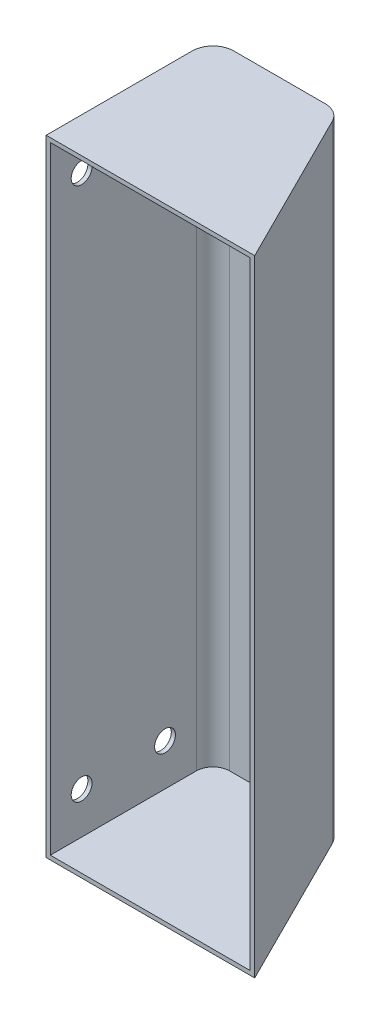
SolidWorks part; units mm, degrees
material "6061-T6 (SS)"
ref_plane "Front Plane" through (0, 0, 0) normal (1, 0, 0) x (0, 1, 0)
ref_plane "Top Plane" through (0, 0, 0) normal (0, 0, 1) x (0, 1, 0)
ref_plane "Right Plane" through (0, 0, 0) normal (0, 1, 0) x (-1, 0, 0)
sketch "Sketch2" plane through (0, 0, 0) normal (0, 1, 0) x (-1, 0, 0)
  line L0 (0, -1430.1125) -> (0, 70075.5127) construction
  line L1 (-1430.1125, 0) -> (70075.5127, 0) construction
  line L2 (0, 40) -> (0, 5)
  line L3 (-5, 0) -> (-26.9098, 0)
  line L4 (-31.382, 2.7639) -> (-50, 40)
  line L5 (-50, 40) -> (0, 40)
  arc A0 (0, 5) -> (-5, 0) centre (-5, 5) cw
  arc A1 (-26.9098, 0) -> (-31.382, 2.7639) centre (-26.9098, 5) cw
  point P7 (0, 0)
  point P10 (-31.5304, 0)
  point P11 (-49.8113, 40)
  point P14 (0, 0)
  point P17 (-30, 0)
  dimension "D4" = 5
  dimension "D1" = 40
  dimension "D2" = 30
  dimension "D3" = 50
extrude "Boss-Extrude1" add sketch "Sketch2" along normal mid plane 150
shell "Shell1" thickness 1
sketch "Sketch3" plane through (1, 0, 0) normal (1, 0, 0) x (0, 1, 0)
  line L0 (0, -1000) -> (0, 49000) construction
  line L1 (-1000, 22.5) -> (49000, 22.5) construction
  line L4 (-74, 40) -> (-74, 5)
  line L5 (-74, 5) -> (74, 5)
  line L6 (74, 5) -> (74, 40)
  line L7 (74, 40) -> (-74, 40)
  line L8 (-74, 40) -> (-74, 5) construction
  line L9 (-74, 5) -> (74, 5) construction
  line L10 (74, 5) -> (74, 40) construction
  line L11 (74, 40) -> (-74, 40) construction
  circle A0 centre (-64, 32.5) radius 2.5
  circle A1 centre (-64, 12.5) radius 2.5
  circle A2 centre (64, 12.5) radius 2.5
  circle A3 centre (64, 32.5) radius 2.5
  point P10 (74, 22.5)
  dimension "D4" = 5
  dimension "D2" = 10
  dimension "D3" = 10
  dimension "D1" = 0
extrude "Cut-Extrude1" cut sketch "Sketch3" against normal up to next
